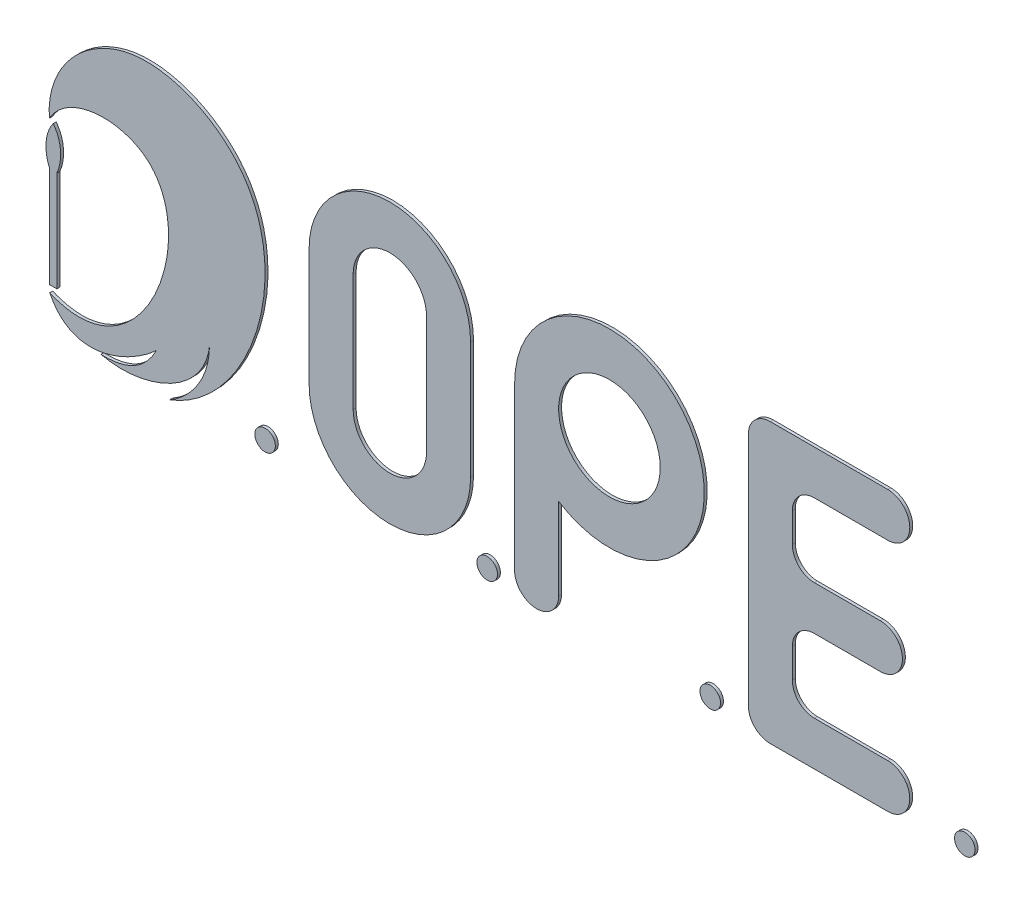
SolidWorks part; units mm, degrees
ref_plane "Front Plane" through (0, 0, 0) normal (0, 0, 1) x (1, 0, 0)
ref_plane "Top Plane" through (0, 0, 0) normal (0, 1, 0) x (1, 0, 0)
ref_plane "Right Plane" through (0, 0, 0) normal (1, 0, 0) x (0, 0, -1)
sketch "Sketch1" plane through (0, 0, 0) normal (0, 0, 1) x (1, 0, 0)
  line L0 (-13.2674, 3.8623) -> (-13.2674, -30.2796)
  line L1 (-13.2674, -30.2796) -> (-10.8394, -30.2796)
  line L2 (-10.8394, -30.2796) -> (-10.8394, 3.8623)
  line L4 (-12.0534, 3.8623) -> (-12.0534, 18.9287) construction
  line L5 (102.5917, 24.5845) -> (102.5917, -15.4155) construction
  line L6 (130.0917, 24.5845) -> (130.0917, -15.4155)
  line L7 (75.0917, 24.5845) -> (75.0917, -15.4155)
  line L8 (102.5917, 24.5845) -> (102.5917, -15.4155) construction
  line L9 (115.0917, 24.5845) -> (115.0917, -15.4155)
  line L10 (90.0917, 24.5845) -> (90.0917, -15.4155)
  line L11 (60.0917, -39.4155) -> (325.8739, -39.4155) construction
  line L12 (145.0917, 19.7783) -> (145.0917, -35.4155)
  line L13 (232.2042, 52.0845) -> (272.2042, 52.0845)
  line L14 (160.0917, -35.4155) -> (160.0917, -7.5015)
  line L15 (160.0917, 19.7783) -> (160.0917, 19.7783)
  line L17 (-14.5559, -42.9155) -> (386.3731, -42.9155) construction
  line L19 (272.2042, 37.0845) -> (247.2042, 37.0845)
  line L20 (239.7042, 29.5845) -> (239.7042, 19.5845)
  line L21 (247.2042, 12.0845) -> (269.7042, 12.0845)
  line L23 (269.7042, -2.9155) -> (247.2042, -2.9155)
  line L24 (239.7042, -10.4155) -> (239.7042, -20.4155)
  line L25 (247.2042, -27.9155) -> (272.2042, -27.9155)
  line L27 (272.2042, -42.9155) -> (232.2042, -42.9155)
  line L28 (224.7042, -35.4155) -> (224.7042, 44.5845)
  line L29 (-34.0446, 52.0845) -> (344.552, 52.0845) construction
  line L30 (60.0917, 27.7117) -> (60.0917, -21.4594) construction
  line L31 (209.7042, 37.4986) -> (209.7042, -6.7672) construction
  arc A1 (130.0917, 24.5845) -> (75.0917, 24.5845) centre (102.5917, 24.5845) ccw
  arc A2 (75.0917, -15.4155) -> (130.0917, -15.4155) centre (102.5917, -15.4155) ccw
  arc A3 (115.0917, 24.5845) -> (90.0917, 24.5845) centre (102.5917, 24.5845) ccw
  arc A4 (90.0917, -15.4155) -> (115.0917, -15.4155) centre (102.5917, -15.4155) ccw
  circle A5 centre (60.0917, -39.4155) radius 3.5
  circle A6 centre (135.7568, -39.4155) radius 3.5
  circle A7 centre (211.7399, -39.4155) radius 3.5
  circle A8 centre (298.4487, -39.4155) radius 3.5
  circle A9 centre (177.398, 19.7783) radius 17.3062
  arc A10 (160.0917, -7.5015) -> (145.0917, 19.7783) centre (177.398, 19.7783) ccw
  arc A11 (160.0917, -35.4155) -> (145.0917, -35.4155) centre (152.5917, -35.4155) cw
  arc A12 (269.7042, 12.0845) -> (269.7042, -2.9155) centre (269.7042, 4.5845) cw
  arc A13 (272.2042, -27.9155) -> (272.2042, -42.9155) centre (272.2042, -35.4155) cw
  arc A14 (272.2042, 52.0845) -> (272.2042, 37.0845) centre (272.2042, 44.5845) cw
  arc A15 (247.2042, -2.9155) -> (239.7042, -10.4155) centre (247.2042, -10.4155) ccw
  arc A16 (247.2042, 37.0845) -> (239.7042, 29.5845) centre (247.2042, 29.5845) ccw
  arc A17 (232.2042, 52.0845) -> (224.7042, 44.5845) centre (232.2042, 44.5845) ccw
  arc A18 (224.7042, -35.4155) -> (232.2042, -42.9155) centre (232.2042, -35.4155) ccw
  arc A19 (239.7042, -20.4155) -> (247.2042, -27.9155) centre (247.2042, -20.4155) ccw
  arc A20 (239.7042, 19.5845) -> (247.2042, 12.0845) centre (247.2042, 19.5845) ccw
  spline S0 degree 3 poles (-13.3991, 18.7617) (-7.1233, 29.8733) (48.6216, 32.825) (18.5239, -46.1846) (-13.2674, -32.6335) knots 0 0 0 0 0.318657 1 1 1 1
  spline S1 degree 3 poles (-13.3991, 18.7617) (-14.596, 34.7863) (10.5539, 61.6559) (77.7704, 31.9194) (54.9355, -33.5011) (27.607, -43.7687) knots 0 0 0 0 0.258385 0.488789 1 1 1 1
  spline S2 degree 3 poles (-13.2674, -32.6335) (-5.3808, -48.6874) (13.7985, -40.1678) (23.1043, -31.4403) knots 0 0 0 0 1 1 1 1
  spline S3 degree 2 poles (23.1043, -31.4403) (17.4252, -42.6436) (4.177, -42.0782) knots 0 0 0 1 1 1
  spline S4 degree 3 poles (4.177, -42.0782) (18.3951, -45.6825) (39.336, -37.4518) (41.1283, -21.2053) knots 0 0 0 0 1 1 1 1
  spline S5 degree 3 poles (41.1283, -21.2053) (41.2089, -30.3889) (35.5167, -39.241) (27.607, -43.7687) knots 0 0 0 0 1 1 1 1
  spline S6 degree 3 poles (-10.8394, 3.8623) (-8.8576, 8.3296) (-9.0669, 13.9102) (-12.0534, 17.8886) knots 0 0 0 0 1 1 1 1
  spline S7 degree 3 poles (-13.2674, 3.8623) (-15.2492, 8.3296) (-15.0399, 13.9102) (-12.0534, 17.8886) knots 0 0 0 0 1 1 1 1
  point P30 (102.5917, 4.5845)
  point P37 (102.5917, 4.5845)
  dimension "D1" = 7
  dimension "D3" = 15
  dimension "D5" = 15
  dimension "D11" = 15
  dimension "D12" = 15
  dimension "D13" = 15
  dimension "D14" = 15
  dimension "D15" = 15
  dimension "D16" = 15
  dimension "D10" = 15
  dimension "D19" = 7
  dimension "D20" = 7
  dimension "D21" = 7
  dimension "D23" = 10
  dimension "D25" = 15
  dimension "D27" = 15
  dimension "D2" = 15
  dimension "D4" = 15
  dimension "D6" = 15
  dimension "D7" = 15
  dimension "D8" = 40
  dimension "D9" = 40
  dimension "D17" = 22.5
  dimension "D18" = 25
  dimension "D22" = 55
  dimension "D24" = 10
  dimension "D26" = 15
  dimension "D28" = 15
extrude "Boss-Extrude2" add sketch "Sketch1" along normal blind 1 contours S4 S5 S1 S0 S2 S3 | L7 A2 L6 A1 A4 L10 A3 L9 | A11 L14 A10 L12 A9 | A20 L20 A16 L19 A14 L13 A17 L28 A18 L27 A13 L25 A19 L24 A15 L23 A12 L21 | A5 | A7 | A8 | A6 | L2 S6 S7 L0 L1
